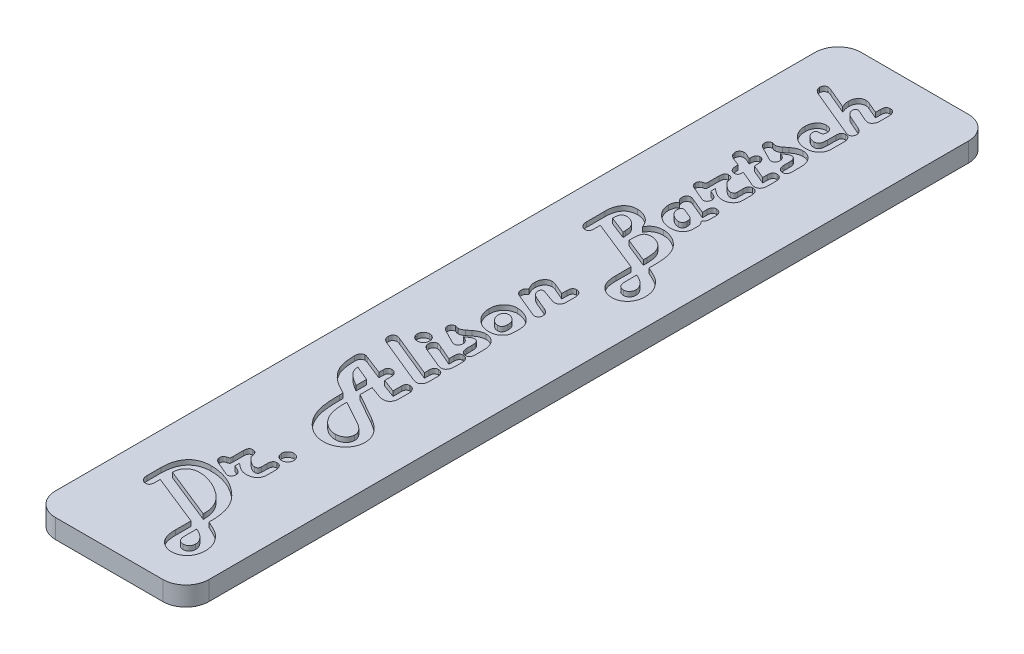
SolidWorks part; units mm, degrees
ref_plane "Front Plane" through (0, 0, 0) normal (0, 0, 1) x (1, 0, 0)
ref_plane "Top Plane" through (0, 0, 0) normal (0, 1, 0) x (1, 0, 0)
ref_plane "Right Plane" through (0, 0, 0) normal (1, 0, 0) x (0, 0, -1)
sketch "Sketch1" plane through (0, 0, 0) normal (0, 0, 1) x (1, 0, 0)
  line L0 (0, 1.5875) -> (0, -1.5875)
  line L1 (-12.7, 0) -> (12.7, 0) construction
  point P6 (0, 0)
  dimension "Width" = 25.4
  dimension "Thk" = 3.175
sketch "Sketch2" plane through (0, 0, 0) normal (1, 0, 0) x (0, 0, -1)
  line L0 (66.675, 0) -> (-66.675, 0)
  point P4 (0, 0)
  dimension "Length" = 133.35
sketch "Sketch3" plane through (0, 0, 0) normal (0, 0, 1) x (1, 0, 0)
  line L1 (12.7, 1.5875) -> (-12.7, 1.5875)
  line L2 (12.7, 1.5875) -> (12.7, -1.5875)
  line L3 (12.7, -1.5875) -> (-12.7, -1.5875)
  line L4 (-12.7, 1.5875) -> (-12.7, -1.5875)
  line L5 (12.7, 1.5875) -> (-12.7, -1.5875) construction
  line L6 (12.7, -1.5875) -> (-12.7, 1.5875) construction
  point P0 (0, 0)
extrude "Boss-Extrude1" add sketch "Sketch3" along normal up to vertex (66.675 mm away) and the other way up to vertex (66.675 mm away) up to point (0, 0, 66.675) other way up to point (0, 0, -66.675)
sketch "Sketch5" plane through (0, 1.5875, 0) normal (0, 1, 0) x (1, 0, 0)
  line L0 (-9.398, 66.929) -> (9.652, 66.929) construction
  line L1 (12.954, 63.627) -> (12.954, -63.373) construction
  line L2 (9.652, -66.675) -> (-9.398, -66.675) construction
  line L3 (-12.7, -63.373) -> (-12.7, 63.627) construction
  line L12 (12.7, -66.675) -> (12.7, 66.675)
  line L13 (12.7, 66.675) -> (-12.7, 66.675)
  line L14 (-12.7, 66.675) -> (-12.7, -66.675)
  line L15 (-12.7, -66.675) -> (12.7, -66.675)
  line L16 (12.7, -62.865) -> (12.7, 62.865)
  line L17 (8.89, 66.675) -> (-8.89, 66.675)
  line L18 (-12.7, 62.865) -> (-12.7, -62.865)
  line L19 (-8.89, -66.675) -> (8.89, -66.675)
  arc A0 (9.652, -66.675) -> (12.954, -63.373) centre (9.652, -63.373) ccw construction
  arc A1 (9.652, -66.675) -> (12.954, -63.373) centre (9.652, -63.373) ccw construction
  arc A2 (-12.7, -63.373) -> (-9.398, -66.675) centre (-9.398, -63.373) ccw construction
  arc A3 (-12.7, -63.373) -> (-9.398, -66.675) centre (-9.398, -63.373) ccw construction
  arc A4 (12.954, 63.627) -> (9.652, 66.929) centre (9.652, 63.627) ccw construction
  arc A5 (12.954, 63.627) -> (9.652, 66.929) centre (9.652, 63.627) ccw construction
  arc A6 (-9.398, 66.929) -> (-12.7, 63.627) centre (-9.398, 63.627) ccw construction
  arc A7 (-9.398, 66.929) -> (-12.7, 63.627) centre (-9.398, 63.627) ccw construction
  arc A8 (12.7, 62.865) -> (8.89, 66.675) centre (8.89, 62.865) ccw
  arc A9 (-8.89, 66.675) -> (-12.7, 62.865) centre (-8.89, 62.865) ccw
  arc A10 (12.7, -62.865) -> (8.89, -66.675) centre (8.89, -62.865) cw
  arc A11 (-8.89, -66.675) -> (-12.7, -62.865) centre (-8.89, -62.865) cw
  dimension "D2" = 3.81
  dimension "D1" = 0
extrude "Cut-Extrude2" cut sketch "Sketch5" against normal through all flip side to cut
sketch "Sketch4" plane through (0, 1.5875, 0) normal (0, 1, 0) x (1, 0, 0)
  line L0 (0, 0) -> (2.54, 0) construction
  line L1 (2.54, -66.675) -> (2.54, 66.675) construction
  line L2 (8.89, 66.675) -> (-8.89, 66.675) construction
  text T0 "Dr. Alison Bartsch" font "Harlow Solid Italic" height 10
  point P8 (2.54, 0)
  dimension "D1" = 2.54
extrude "Cut-Extrude1" cut sketch "Sketch4" against normal blind 0.7937
